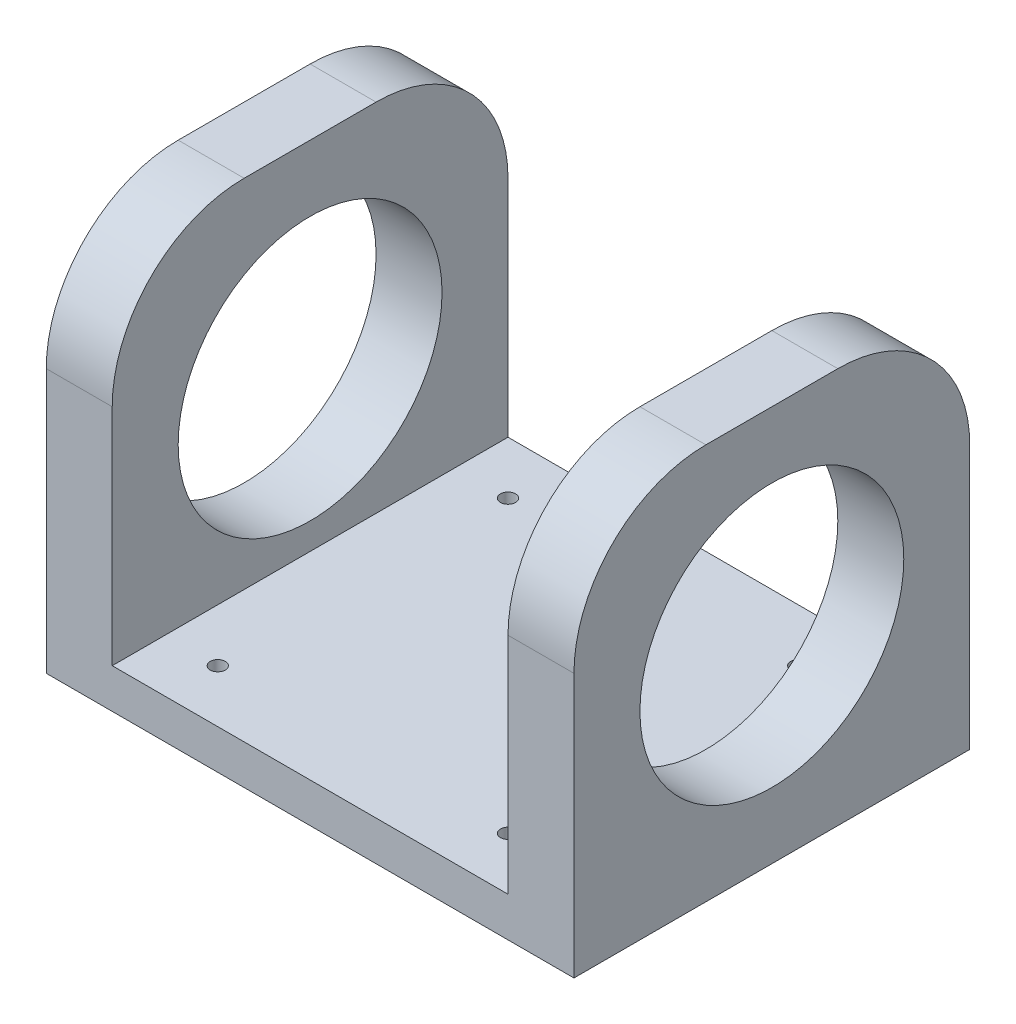
SolidWorks part; units mm, degrees
ref_plane "Front Plane" through (0, 0, 0) normal (0, 0, 1) x (1, 0, 0)
ref_plane "Top Plane" through (0, 0, 0) normal (0, 1, 0) x (1, 0, 0)
ref_plane "Right Plane" through (0, 0, 0) normal (1, 0, 0) x (0, 0, -1)
sketch "Sketch1" plane through (0, 0, 0) normal (0, 1, 0) x (1, 0, 0)
  line L1 (50.8, 38.1) -> (-50.8, 38.1)
  line L2 (50.8, 38.1) -> (50.8, -38.1)
  line L3 (50.8, -38.1) -> (-50.8, -38.1)
  line L4 (-50.8, 38.1) -> (-50.8, -38.1)
  line L5 (0, -38.1) -> (0, 38.1) construction
  line L6 (50.8, 0) -> (-50.8, 0) construction
  point P0 (0, 0)
  dimension "D1" = 76.2
  dimension "4" = 101.6
extrude "Boss-Extrude1" add sketch "Sketch1" against normal blind 30.48
sketch "Sketch2" plane through (-50.8, 0, 0) normal (-1, 0, 0) x (0, 0, 1)
  line L1 (-38.1, -30.48) -> (38.1, -30.48)
  line L2 (-38.1, -30.48) -> (-38.1, 20.32)
  line L3 (-12.7, 45.72) -> (12.7, 45.72)
  line L4 (38.1, -30.48) -> (38.1, 20.32)
  line L5 (-38.1, -30.48) -> (38.1, 45.72) construction
  line L6 (-38.1, 45.72) -> (38.1, -30.48) construction
  circle A0 centre (0, 7.62) radius 25.4
  arc A1 (12.7, 45.72) -> (38.1, 20.32) centre (12.7, 20.32) cw
  arc A2 (-38.1, 20.32) -> (-12.7, 45.72) centre (-12.7, 20.32) cw
  point P4 (0, 7.62)
  dimension "D3" = 50.8
  dimension "D4" = 25.4
  dimension "D1" = 76.2
  dimension "D2" = 76.2
extrude "Boss-Extrude2" add sketch "Sketch2" against normal blind 12.7
mirror "Mirror1" about plane through (0, 0, 0) normal (1, 0, 0) of "Boss-Extrude2"
sketch "Sketch3" plane through (0, 0, 0) normal (0, 1, 0) x (1, 0, 0)
  line L1 (-38.1, 38.1) -> (38.1, 38.1)
  line L2 (-38.1, 38.1) -> (-38.1, -38.1)
  line L3 (-38.1, -38.1) -> (38.1, -38.1)
  line L4 (38.1, 38.1) -> (38.1, -38.1)
  line L5 (-38.1, 38.1) -> (38.1, -38.1) construction
  line L6 (-38.1, -38.1) -> (38.1, 38.1) construction
  point P4 (0, 0)
extrude "Cut-Extrude1" cut sketch "Sketch3" against normal blind 22.86
sketch "Sketch5" plane through (-50.8, 0, 0) normal (-1, 0, 0) x (0, 0, 1)
  circle A0 centre (0, 7.62) radius 25.4
  dimension "D1" = 50.8
  dimension "D2" = 7.62
extrude "Cut-Extrude3" cut sketch "Sketch5" against normal blind 256.032
sketch "Sketch6" plane through (0, -22.86, 0) normal (0, 1, 0) x (1, 0, 0)
  line L0 (38.1, 38.1) -> (-38.1, 38.1) construction
  line L1 (-38.1, 38.1) -> (-38.1, -38.1) construction
  line L3 (0, -41.91) -> (0, 41.91) construction
  line L4 (-41.91, 0) -> (41.91, 0) construction
  circle A0 centre (-27.94, 27.94) radius 1.45
  circle A1 centre (27.94, 27.94) radius 1.45
  circle A2 centre (27.94, -27.94) radius 1.45
  circle A3 centre (-27.94, -27.94) radius 1.45
  dimension "D3" = 2.9
  dimension "D1" = 10.16
  dimension "D2" = 10.16
extrude "Cut-Extrude4" cut sketch "Sketch6" against normal blind 256.032
